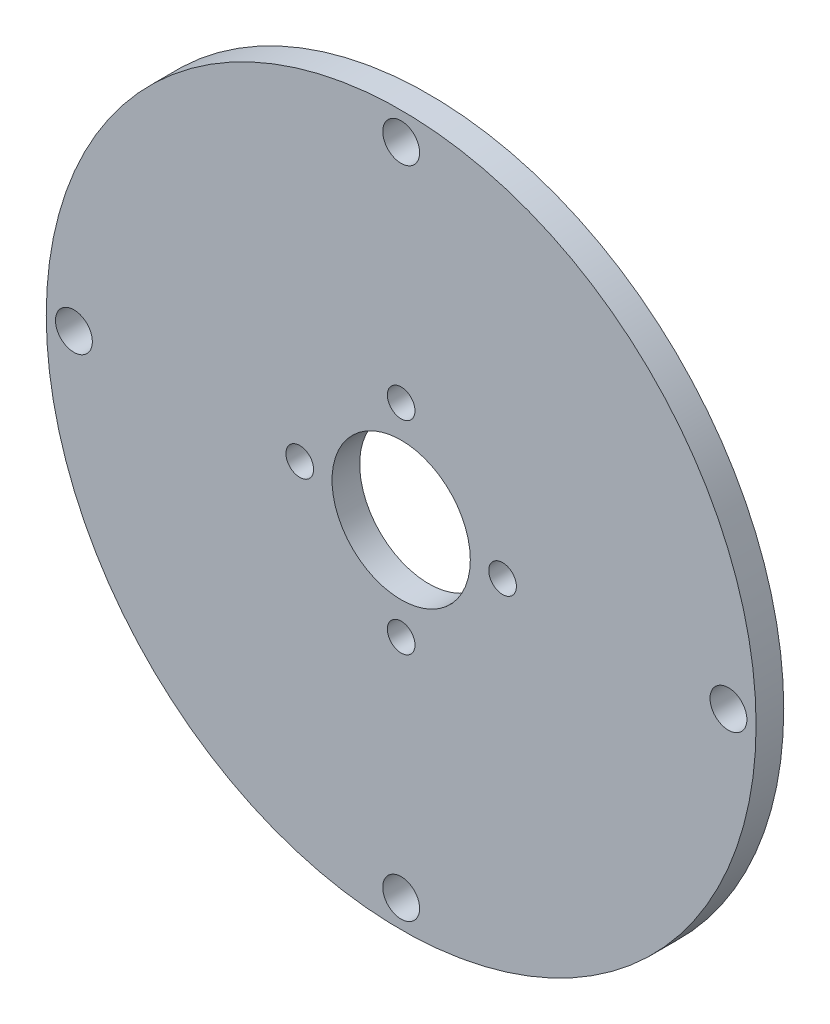
SolidWorks part; units mm, degrees
material "Thornel Mat VMA"
ref_plane "Front" through (0, 0, 0) normal (0, 0, 1) x (1, 0, 0)
ref_plane "Top" through (0, 0, 0) normal (0, 1, 0) x (1, 0, 0)
ref_plane "Right" through (0, 0, 0) normal (1, 0, 0) x (0, 0, -1)
sketch "Sketch1" plane through (0, 0, 0) normal (0, 0, 1) x (1, 0, 0)
  line L0 (0, 0) -> (0, 11) construction
  circle A0 centre (0, 0) radius 38.5
  circle A1 centre (0, 11) radius 1.5
  circle A2 centre (0, 35.5) radius 2
  circle A3 centre (35.5, 0) radius 2
  circle A4 centre (11, 0) radius 1.5
  circle A5 centre (0, -35.5) radius 2
  circle A6 centre (0, -11) radius 1.5
  circle A7 centre (-35.5, 0) radius 2
  circle A8 centre (-11, 0) radius 1.5
  circle A9 centre (0, 0) radius 7.5
  point P22 (0, 0)
  dimension "D1" = 77
  dimension "D2" = 11
  dimension "D3" = 35.5
  dimension "D5" = 3
  dimension "D6" = 15
  dimension "D4" = 4
extrude "Boss-Extrude1" add sketch "Sketch1" along normal blind 3
